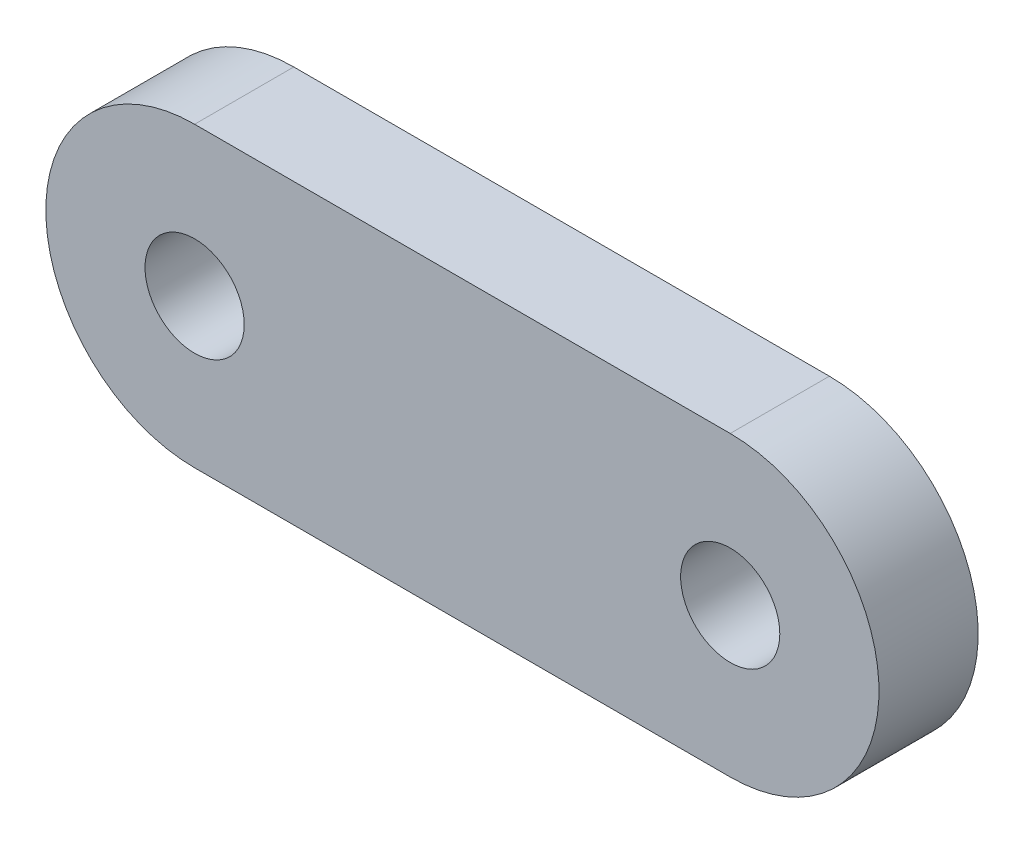
SolidWorks part; units mm, degrees
ref_plane "Alzado" through (0, 0, 0) normal (0, 0, 1) x (1, 0, 0)
ref_plane "Planta" through (0, 0, 0) normal (0, 1, 0) x (1, 0, 0)
ref_plane "Vista lateral" through (0, 0, 0) normal (1, 0, 0) x (0, 0, -1)
ref_plane "Plano1" through (0, 0, 0) normal (0, 0, -1) x (-1, 0, 0)
sketch "Croquis3" plane through (0, 0, 0) normal (0, 0, 1) x (1, 0, 0)
  line L0 (0, 0) -> (10.8, 0) construction
  line L1 (0, 3) -> (10.8, 3)
  line L2 (0, -3) -> (10.8, -3)
  arc A0 (0, 3) -> (0, -3) centre (0, 0) ccw
  arc A1 (10.8, -3) -> (10.8, 3) centre (10.8, 0) ccw
  circle A2 centre (0, 0) radius 1
  circle A3 centre (10.8, 0) radius 1
  point P3 (5.4, 0)
  point P8 (13.8, 0)
  point P9 (-3, 0)
  dimension "D3" = 2
  dimension "D4" = 2
  dimension "D1" = 16.8
  dimension "D2" = 6
extrude "Saliente-Extruir1" add sketch "Croquis3" along normal blind 2
